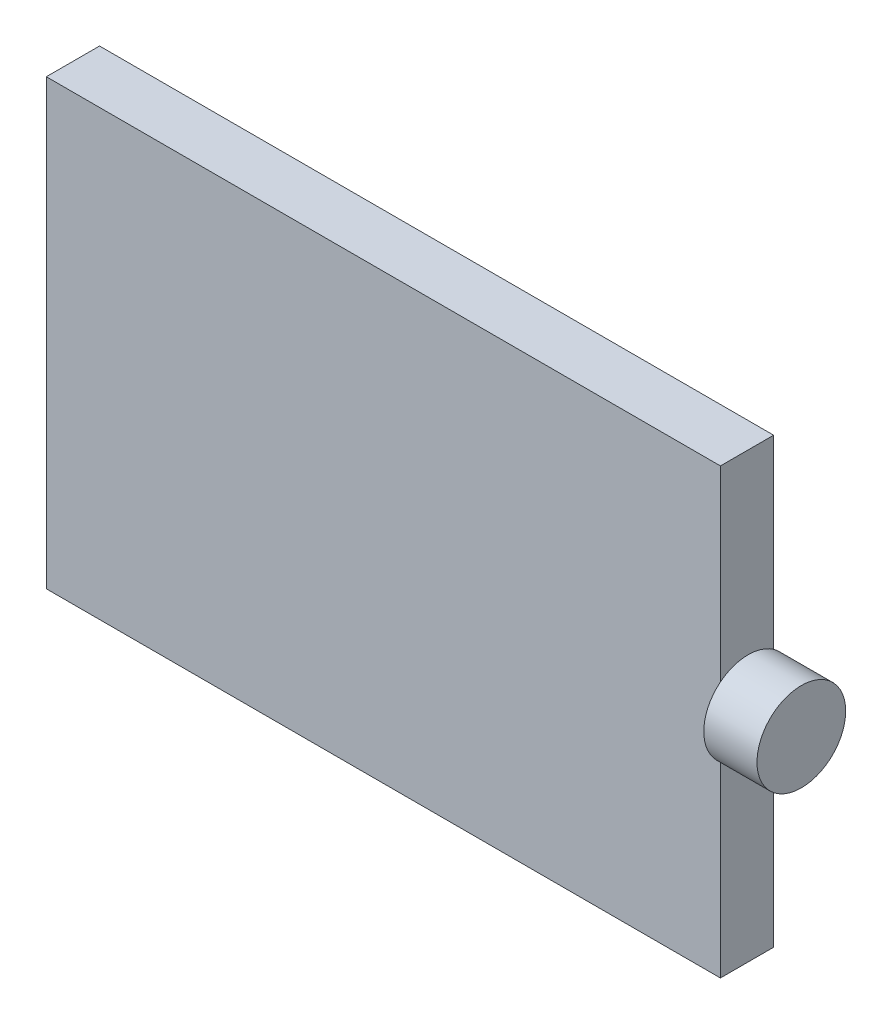
SolidWorks part; units mm, degrees
material "ABS"
ref_plane "Front Plane" through (0, 0, 0) normal (0, 0, 1) x (1, 0, 0)
ref_plane "Top Plane" through (0, 0, 0) normal (0, 1, 0) x (1, 0, 0)
ref_plane "Right Plane" through (0, 0, 0) normal (1, 0, 0) x (0, 0, -1)
sketch "Sketch2" plane through (0, 0, 0) normal (0, 0, 1) x (1, 0, 0)
  line L1 (-19, -12.5) -> (19, -12.5)
  line L2 (-19, -12.5) -> (-19, 12.5)
  line L3 (-19, 12.5) -> (19, 12.5)
  line L4 (19, -12.5) -> (19, 12.5)
  line L5 (-19, -12.5) -> (19, 12.5) construction
  line L6 (-19, 12.5) -> (19, -12.5) construction
  point P0 (0, 0)
  dimension "D1" = 38
  dimension "D2" = 25
extrude "Boss-Extrude1" add sketch "Sketch2" along normal blind 3
sketch "Sketch3" plane through (19, 0, 0) normal (1, 0, 0) x (0, 0, -1)
  circle A0 centre (-1.4379, 0) radius 2.5
  dimension "D1" = 5
extrude "Boss-Extrude2" add sketch "Sketch3" along normal blind 3
